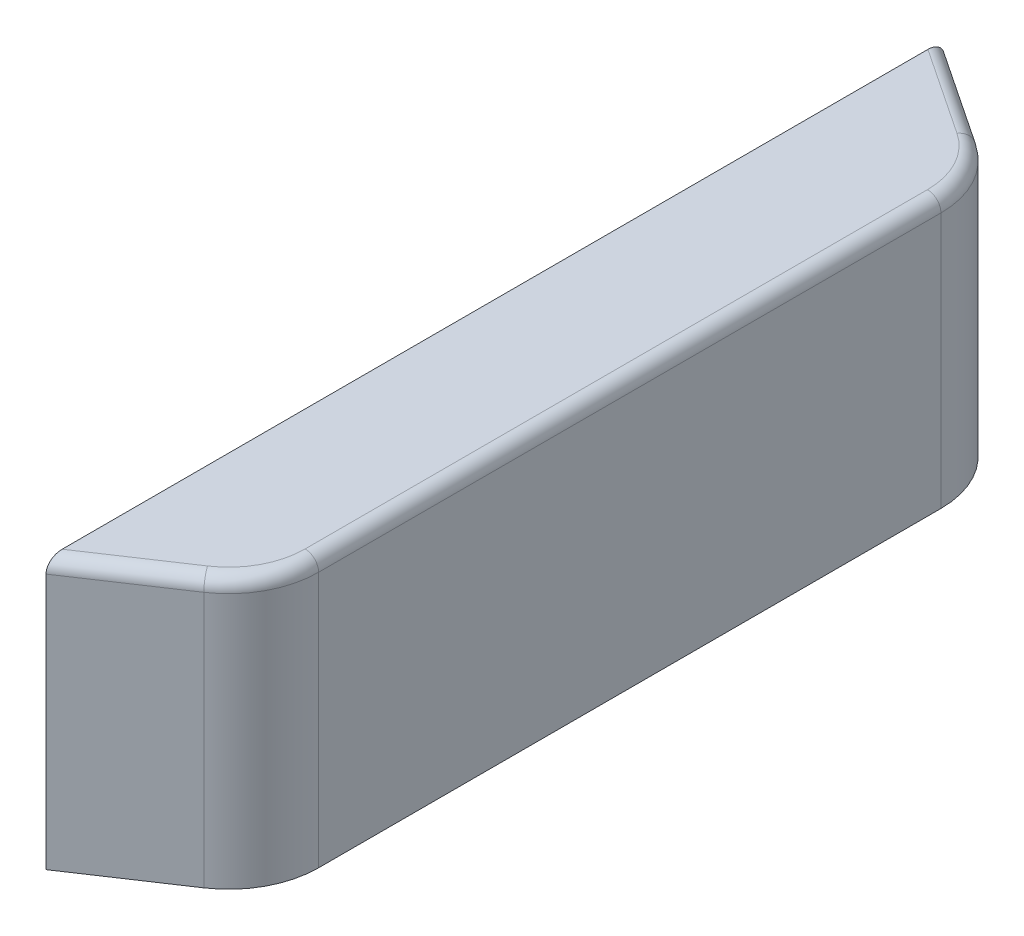
SolidWorks part; units mm, degrees
ref_plane "Front Plane" through (0, 0, 0) normal (0, 0, 1) x (1, 0, 0)
ref_plane "Top Plane" through (0, 0, 0) normal (0, 1, 0) x (1, 0, 0)
ref_plane "Right Plane" through (0, 0, 0) normal (1, 0, 0) x (0, 0, -1)
sketch "Sketch1" plane through (0, 0, 0) normal (0, 1, 0) x (1, 0, 0)
  line L0 (0, -50) -> (0, 50)
  line L1 (15, -34.6482) -> (15, 34.6482)
  line L2 (0, 50) -> (10.547, 42.9687)
  line L3 (10.547, -42.9687) -> (0, -50)
  line L4 (0, 0) -> (15, 0) construction
  arc A0 (10.547, -42.9687) -> (15, -34.6482) centre (5, -34.6482) ccw
  arc A1 (10.547, 42.9687) -> (15, 34.6482) centre (5, 34.6482) cw
  point P4 (0, 0)
  point P8 (15, 0)
  point P12 (15, -40)
  point P15 (15, 40)
  dimension "D4" = 10
  dimension "D1" = 15
  dimension "D2" = 80
  dimension "D3" = 100
extrude "Boss-Extrude1" add sketch "Sketch1" along normal blind 30
shell "Shell1" thickness 1.5
fillet "Fillet1" radius 2 8 edges at (1.5, 28.5, 0) (5.6075, 28.5, 44.4589) (12.4942, 28.5, 38.659) (13.5, 28.5, 0) (12.4942, 28.5, -38.659) (5.6075, 28.5, -44.4589) (1.5, 14.25, -47.1972) (1.5, 14.25, 47.1972)
fillet "Fillet2" radius 1.5 5 edges at (5.2735, 30, 46.4843) (13.8167, 30, 39.3667) (5.2735, 30, -46.4843) (13.8167, 30, -39.3667) (15, 30, 0)
